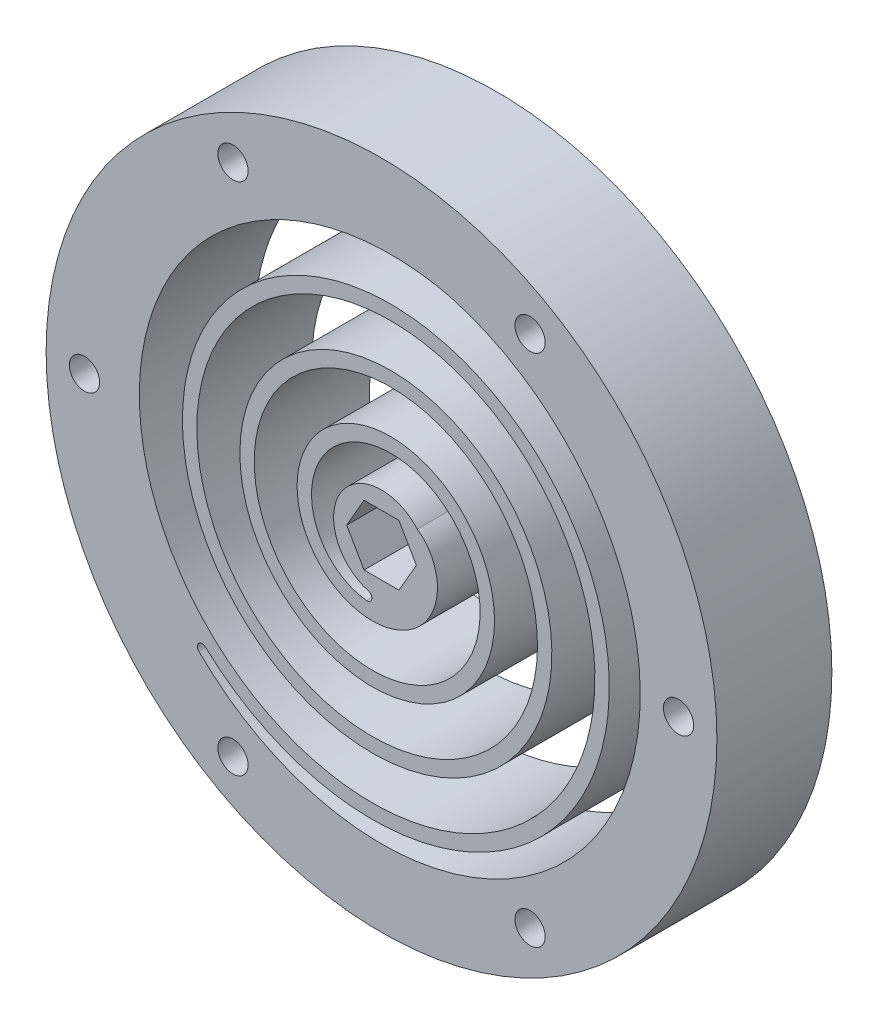
SolidWorks part; units mm, degrees
material "ASTM A36 Steel"
ref_plane "Front Plane" through (0, 0, 0) normal (0, 0, 1) x (1, 0, 0)
ref_plane "Top Plane" through (0, 0, 0) normal (0, 1, 0) x (1, 0, 0)
ref_plane "Right Plane" through (0, 0, 0) normal (1, 0, 0) x (0, 0, -1)
sketch "Sketch1" plane through (0, 0, 0) normal (0, 0, 1) x (1, 0, 0)
  line L1 (1.8187, 3.15) -> (-1.8187, 3.15)
  line L2 (-1.8187, 3.15) -> (-3.6373, 0)
  line L3 (-3.6373, 0) -> (-1.8187, -3.15)
  line L4 (-1.8187, -3.15) -> (1.8187, -3.15)
  line L5 (1.8187, -3.15) -> (3.6373, 0)
  line L6 (3.6373, 0) -> (1.8187, 3.15)
  circle A0 centre (0, 0) radius 35
  circle A1 centre (0, 0) radius 31 construction
  circle A2 centre (0, 0) radius 27
  circle A3 centre (0, 0) radius 5
  circle A4 centre (0, 0) radius 3.15 construction
  point P6 (0, 0)
  dimension "D1" = 6.3
  dimension "Spring OD" = 54
  dimension "Spring Body OD" = 70
  dimension "Bolt Centerline" = 62
  dimension "Spring ID" = 10
sketch "Sketch2" plane through (0, 0, 0) normal (0, 0, 1) x (1, 0, 0)
  line L1 (3.6373, 0) -> (1.8187, 3.15)
  line L2 (1.8187, 3.15) -> (-1.8187, 3.15)
  line L3 (-1.8187, 3.15) -> (-3.6373, 0)
  line L4 (-3.6373, 0) -> (-1.8187, -3.15)
  line L5 (-1.8187, -3.15) -> (1.8187, -3.15)
  line L6 (1.8187, -3.15) -> (3.6373, 0)
  circle A0 centre (0, 0) radius 35
  circle A1 centre (0, 0) radius 27
  circle A2 centre (0, 0) radius 5
  circle A3 centre (0, 0) radius 5 construction
  circle A4 centre (0, 0) radius 27 construction
  circle A5 centre (0, 0) radius 35 construction
  circle A6 centre (0, 0) radius 3.15 construction
  circle A7 centre (-31, 0) radius 1.58
  circle A8 centre (0, 0) radius 31 construction
  circle A9 centre (-15.5, 26.8468) radius 1.58
  circle A10 centre (15.5, 26.8468) radius 1.58
  circle A11 centre (31, 0) radius 1.58
  circle A12 centre (15.5, -26.8468) radius 1.58
  circle A13 centre (-15.5, -26.8468) radius 1.58
  point P11 (-33.4053, 32.4641)
  point P24 (0, 0)
  point P36 (0, 0)
  dimension "D1" = 3.16
  dimension "D2" = 6
extrude "Boss-Extrude1" add sketch "Sketch2" along normal blind 12 contours A0 A13 A12 A11 A10 A9 A7 A1 | A2 L6 L5 L4 L3 L2 L1
sketch "Sketch3" plane through (0, 0, 0) normal (0, 0, 1) x (1, 0, 0)
  circle A0 centre (0, 0) radius 5
  circle A1 centre (0, 0) radius 5 construction
curve "Helix/Spiral1"
sketch "Sketch6" plane through (0, 0, 0) normal (0, 0, 1) x (1, 0, 0)
  circle A0 centre (0, 0) radius 5 construction
  arc A1 (3.4915, -3.5791) -> (3.7422, 3.3161) centre (0, 0) ccw
  arc A2 (7.0031, 26.076) -> (-26.083, 6.977) centre (0, 0) ccw
  circle A3 centre (0, 0) radius 27 construction
  spline S2 degree 3 poles (656.0344, -3941.2943) (-203.1406, 58.5302) (9.6748, 22.8003) (4.1017, -2.4931) (3.8402, -3.0922) (3.0715, -4.167) (2.5594, -4.6491) (1.3478, -5.3876) (0.6412, -5.6477) (-0.8593, -5.8682) (-1.6609, -5.8292) (-3.2231, -5.4225) (-3.9909, -5.0525) (-5.3491, -4.0104) (-5.9453, -3.3335) (-6.8402, -1.7606) (-7.1423, -0.8581) (-7.3683, 1.0359) (-7.2928, 2.0345) (-6.7403, 3.9621) (-6.2609, 4.8977) (-4.944, 6.5373) (-4.1017, 7.2465) (-2.1671, 8.2957) (-1.0685, 8.6388) (1.2185, 8.8687) (2.414, 8.7559) (4.706, 8.0561) (5.8091, 7.4669) (7.7289, 5.8743) (8.5506, 4.8664) (9.753, 2.5699) (10.1365, 1.2752) (10.3691, -1.4049) (10.2185, -2.797) (9.3708, -5.453) (8.6713, -6.7232) (6.8026, -8.9225) (5.6288, -9.8564) (2.9702, -11.2112) (1.4793, -11.6348) (-1.5936, -11.8696) (-3.1822, -11.6808) (-6.202, -10.6846) (-7.6391, -9.8747) (-10.1175, -7.7295) (-11.1633, -6.3898) (-12.6701, -3.3689) (-13.1335, -1.6818) (-13.3699, 1.7839) (-13.1429, 3.569) (-11.9978, 6.9523) (-11.0773, 8.5563) (-8.6554, 11.3135) (-7.1496, 12.471) (-3.7663, 14.1294) (-1.8832, 14.6326) (1.9754, 14.8703) (3.956, 14.6052) (6.7673, 13.634) (7.6787, 13.2154) (9.4111, 12.2011) (10.2329, 11.605) (11.7515, 10.2549) (12.449, 9.5004) (13.6888, 7.8597) (14.2315, 6.9727) (15.1368, 5.099) (15.4997, 4.1114) (16.0269, 2.073) (16.1915, 1.0213) (16.3109, -1.1054) (16.2659, -2.1812) (15.9634, -4.3144) (15.7059, -5.3726) (14.9837, -7.4285) (14.5188, -8.427) (13.3959, -10.323) (12.7374, -11.2212) (11.2488, -12.879) (10.4182, -13.6393) (8.6144, -14.9885) (7.6406, -15.578) (5.5856, -16.5589) (4.5036, -16.9507) (2.2727, -17.5166) (1.1228, -17.691) (-1.2002, -17.811) (-2.3742, -17.7565) (-4.7001, -17.4162) (-5.8528, -17.1301) (-8.0903, -16.3333) (-9.1759, -15.8221) (-11.2353, -14.5904) (-12.2099, -13.8694) (-14.0069, -12.2423) (-14.8299, -11.3355) (-16.2886, -9.3687) (-16.9248, -8.3079) (-17.9812, -6.0717) (-18.4018, -4.8954) (-19.0064, -2.4719) (-19.1907, -1.2239) (-19.311, 1.2955) (-19.2471, 2.5677) (-18.8688, 5.0863) (-18.5543, 6.3334) (-17.6826, 8.7524) (-17.1251, 9.9252) (-15.7846, 12.1481) (-15.0012, 13.199) (-13.2355, 15.1351) (-12.2525, 16.0209) (-10.1226, 17.589) (-8.9749, 18.2718) (-6.5574, 19.4036) (-5.2868, 19.853) (-2.6708, 20.4963) (-1.3246, 20.6904) (1.3912, 20.811) (2.7616, 20.7376) (5.4728, 20.3213) (6.8144, 19.9784) (9.415, 19.0318) (10.6748, 18.4279) (13.0611, 16.9786) (14.1884, 16.1327) (16.2636, 14.2284) (17.2121, 13.1693) (18.8895, 10.8763) (19.6189, 9.6417) (20.8262, 7.0428) (21.3044, 5.6778) (21.9863, 2.8693) (22.1902, 1.4249) (22.3111, -1.4872) (22.2281, -2.9558) (21.7738, -5.8596) (21.4024, -7.2957) (20.3809, -10.0778) (19.7306, -11.4246) (18.1724, -13.9744) (17.2641, -15.1781) (15.2211, -17.3923) (14.0858, -18.4034) (11.6297, -20.1902) (10.3081, -20.9663) (7.528, -22.2489) (6.0686, -22.7558) (3.0675, -23.4763) (1.525, -23.69) (-1.5834, -23.8111) (-3.1503, -23.7186) (-6.2467, -23.2263) (-7.7772, -22.8263) (-10.7408, -21.7299) (-12.1748, -21.0332) (-14.8879, -19.3662) (-16.1679, -18.3953) (-18.5211, -16.2136) (-19.595, -15.0022) (-21.491, -12.3829) (-22.3137, -10.9744) (-23.6717, -8.0129) (-24.2074, -6.4591) (-24.9663, -3.2656) (-25.1898, -1.6249) (-25.3112, 1.6799) (-25.2091, 3.345) (-24.6787, 6.6341) (-24.2501, 8.259) (-23.0788, 11.4041) (-22.3357, 12.925) (-20.5597, 15.8016) (-19.5264, 17.1579) (-17.206, 19.6501) (-15.9184, 20.7866) (-13.136, 22.7919) (-11.6405, 23.6612) (-8.4977, 25.0945) (-6.8495, 25.6589) (-3.4634, 26.4564) (-1.7246, 26.6897) (1.7766, 26.8112) (3.5398, 26.6996) (7.0215, 26.131) (8.7409, 25.6739) (12.0675, 24.4277) (13.6755, 23.6382) (16.7154, 21.7532) (18.1481, 20.6574) (20.7792, 18.1983) (21.9784, 16.8344) (24.0929, 13.8889) (25.0088, 12.3064) (26.5174, 8.9823) (27.1106, 7.2398) (47.698, -80.8932) (-339.5507, -278.2314) (-1939.009, 3446.9436) knots -0.630078 -0.630078 -0.630078 -0.630078 0.015625 0.015625 0.03125 0.03125 0.046875 0.046875 0.0625 0.0625 0.078125 0.078125 0.09375 0.09375 0.109375 0.109375 0.125 0.125 0.140625 0.140625 0.15625 0.15625 0.171875 0.171875 0.1875 0.1875 0.203125 0.203125 0.21875 0.21875 0.234375 0.234375 0.25 0.25 0.265625 0.265625 0.28125 0.28125 0.296875 0.296875 0.3125 0.3125 0.328125 0.328125 0.34375 0.34375 0.359375 0.359375 0.375 0.375 0.390625 0.390625 0.40625 0.40625 0.421875 0.421875 0.4375 0.4375 0.453125 0.453125 0.460938 0.460938 0.46875 0.46875 0.476563 0.476563 0.484375 0.484375 0.492188 0.492188 0.5 0.5 0.507813 0.507813 0.515625 0.515625 0.523438 0.523438 0.53125 0.53125 0.539063 0.539063 0.546875 0.546875 0.554688 0.554688 0.5625 0.5625 0.570313 0.570313 0.578125 0.578125 0.585938 0.585938 0.59375 0.59375 0.601563 0.601563 0.609375 0.609375 0.617188 0.617188 0.625 0.625 0.632813 0.632813 0.640625 0.640625 0.648438 0.648438 0.65625 0.65625 0.664063 0.664063 0.671875 0.671875 0.679688 0.679688 0.6875 0.6875 0.695313 0.695313 0.703125 0.703125 0.710938 0.710938 0.71875 0.71875 0.726563 0.726563 0.734375 0.734375 0.742188 0.742188 0.75 0.75 0.757813 0.757813 0.765625 0.765625 0.773438 0.773438 0.78125 0.78125 0.789063 0.789063 0.796875 0.796875 0.804688 0.804688 0.8125 0.8125 0.820313 0.820313 0.828125 0.828125 0.835938 0.835938 0.84375 0.84375 0.851563 0.851563 0.859375 0.859375 0.867188 0.867188 0.875 0.875 0.882813 0.882813 0.890625 0.890625 0.898438 0.898438 0.90625 0.90625 0.914063 0.914063 0.921875 0.921875 0.929688 0.929688 0.9375 0.9375 0.945312 0.945312 0.953125 0.953125 0.960938 0.960938 0.96875 0.96875 0.976562 0.976562 0.984375 0.984375 0.992188 0.992188 1.369176 1.369176 1.369176 1.369176 only from (4.2633, -0.1407) to (28.2504, -0.0247)
  spline S3 degree 3 poles (3.4915, -3.5791) (3.4797, -3.596) (3.4678, -3.6128) (3.0715, -4.167) (2.5594, -4.6491) (1.3478, -5.3876) (0.6412, -5.6477) (-0.8593, -5.8682) (-1.6609, -5.8292) (-3.2231, -5.4225) (-3.9909, -5.0525) (-5.3491, -4.0104) (-5.9453, -3.3335) (-6.8402, -1.7606) (-7.1423, -0.8581) (-7.3683, 1.0359) (-7.2928, 2.0345) (-6.7403, 3.9621) (-6.2609, 4.8977) (-4.944, 6.5373) (-4.1017, 7.2465) (-2.1671, 8.2957) (-1.0685, 8.6388) (1.2185, 8.8687) (2.414, 8.7559) (4.706, 8.0561) (5.8091, 7.4669) (7.7289, 5.8743) (8.5506, 4.8664) (9.753, 2.5699) (10.1365, 1.2752) (10.3691, -1.4049) (10.2185, -2.797) (9.3708, -5.453) (8.6713, -6.7232) (6.8026, -8.9225) (5.6288, -9.8564) (2.9702, -11.2112) (1.4793, -11.6348) (-1.5936, -11.8696) (-3.1822, -11.6808) (-6.202, -10.6846) (-7.6391, -9.8747) (-10.1175, -7.7295) (-11.1633, -6.3898) (-12.6701, -3.3689) (-13.1335, -1.6818) (-13.3699, 1.7839) (-13.1429, 3.569) (-11.9978, 6.9523) (-11.0773, 8.5563) (-8.6554, 11.3135) (-7.1496, 12.471) (-3.7663, 14.1294) (-1.8832, 14.6326) (1.9754, 14.8703) (3.956, 14.6052) (6.7673, 13.634) (7.6787, 13.2154) (9.4111, 12.2011) (10.2329, 11.605) (11.7515, 10.2549) (12.449, 9.5004) (13.6888, 7.8597) (14.2315, 6.9727) (15.1368, 5.099) (15.4997, 4.1114) (16.0269, 2.073) (16.1915, 1.0213) (16.3109, -1.1054) (16.2659, -2.1812) (15.9634, -4.3144) (15.7059, -5.3726) (14.9837, -7.4285) (14.5188, -8.427) (13.3959, -10.323) (12.7374, -11.2212) (11.2488, -12.879) (10.4182, -13.6393) (8.6144, -14.9885) (7.6406, -15.578) (5.5856, -16.5589) (4.5036, -16.9507) (2.2727, -17.5166) (1.1228, -17.691) (-1.2002, -17.811) (-2.3742, -17.7565) (-4.7001, -17.4162) (-5.8528, -17.1301) (-8.0903, -16.3333) (-9.1759, -15.8221) (-11.2353, -14.5904) (-12.2099, -13.8694) (-14.0069, -12.2423) (-14.8299, -11.3355) (-16.2886, -9.3687) (-16.9248, -8.3079) (-17.9812, -6.0717) (-18.4018, -4.8954) (-19.0064, -2.4719) (-19.1907, -1.2239) (-19.311, 1.2955) (-19.2471, 2.5677) (-18.8688, 5.0863) (-18.5543, 6.3334) (-17.6826, 8.7524) (-17.1251, 9.9252) (-15.7846, 12.1481) (-15.0012, 13.199) (-13.2355, 15.1351) (-12.2525, 16.0209) (-10.1226, 17.589) (-8.9749, 18.2718) (-6.5574, 19.4036) (-5.2868, 19.853) (-2.6708, 20.4963) (-1.3246, 20.6904) (1.3912, 20.811) (2.7616, 20.7376) (5.4728, 20.3213) (6.8144, 19.9784) (9.415, 19.0318) (10.6748, 18.4279) (13.0611, 16.9786) (14.1884, 16.1327) (16.2636, 14.2284) (17.2121, 13.1693) (18.8895, 10.8763) (19.6189, 9.6417) (20.8262, 7.0428) (21.3044, 5.6778) (21.9863, 2.8693) (22.1902, 1.4249) (22.3111, -1.4872) (22.2281, -2.9558) (21.7738, -5.8596) (21.4024, -7.2957) (20.3809, -10.0778) (19.7306, -11.4246) (18.1724, -13.9744) (17.2641, -15.1781) (15.2211, -17.3923) (14.0858, -18.4034) (11.6297, -20.1902) (10.3081, -20.9663) (7.528, -22.2489) (6.0686, -22.7558) (3.0675, -23.4763) (1.525, -23.69) (-1.5834, -23.8111) (-3.1503, -23.7186) (-6.2467, -23.2263) (-7.7772, -22.8263) (-10.7408, -21.7299) (-12.1748, -21.0332) (-14.8879, -19.3662) (-16.1679, -18.3953) (-18.5211, -16.2136) (-19.595, -15.0022) (-21.491, -12.3829) (-22.3137, -10.9744) (-23.6717, -8.0129) (-24.2074, -6.4591) (-24.9663, -3.2656) (-25.1898, -1.6249) (-25.3112, 1.6799) (-25.2091, 3.345) (-24.6787, 6.6341) (-24.2501, 8.259) (-23.0788, 11.4041) (-22.3357, 12.925) (-20.5597, 15.8016) (-19.5264, 17.1579) (-17.206, 19.6501) (-15.9184, 20.7866) (-13.136, 22.7919) (-11.6405, 23.6612) (-8.4977, 25.0945) (-6.8495, 25.6589) (-3.4634, 26.4564) (-1.7246, 26.6897) (1.7766, 26.8112) (3.5398, 26.6996) (5.8576, 26.3211) (6.4322, 26.2079) (7.0031, 26.076) knots 0.030762 0.030762 0.030762 0.030762 0.03125 0.03125 0.046875 0.046875 0.0625 0.0625 0.078125 0.078125 0.09375 0.09375 0.109375 0.109375 0.125 0.125 0.140625 0.140625 0.15625 0.15625 0.171875 0.171875 0.1875 0.1875 0.203125 0.203125 0.21875 0.21875 0.234375 0.234375 0.25 0.25 0.265625 0.265625 0.28125 0.28125 0.296875 0.296875 0.3125 0.3125 0.328125 0.328125 0.34375 0.34375 0.359375 0.359375 0.375 0.375 0.390625 0.390625 0.40625 0.40625 0.421875 0.421875 0.4375 0.4375 0.453125 0.453125 0.460938 0.460938 0.46875 0.46875 0.476563 0.476563 0.484375 0.484375 0.492188 0.492188 0.5 0.5 0.507813 0.507813 0.515625 0.515625 0.523438 0.523438 0.53125 0.53125 0.539063 0.539063 0.546875 0.546875 0.554688 0.554688 0.5625 0.5625 0.570313 0.570313 0.578125 0.578125 0.585938 0.585938 0.59375 0.59375 0.601563 0.601563 0.609375 0.609375 0.617188 0.617188 0.625 0.625 0.632813 0.632813 0.640625 0.640625 0.648438 0.648438 0.65625 0.65625 0.664063 0.664063 0.671875 0.671875 0.679688 0.679688 0.6875 0.6875 0.695313 0.695313 0.703125 0.703125 0.710938 0.710938 0.71875 0.71875 0.726563 0.726563 0.734375 0.734375 0.742188 0.742188 0.75 0.75 0.757813 0.757813 0.765625 0.765625 0.773438 0.773438 0.78125 0.78125 0.789063 0.789063 0.796875 0.796875 0.804688 0.804688 0.8125 0.8125 0.820313 0.820313 0.828125 0.828125 0.835938 0.835938 0.84375 0.84375 0.851563 0.851563 0.859375 0.859375 0.867188 0.867188 0.875 0.875 0.882813 0.882813 0.890625 0.890625 0.898438 0.898438 0.90625 0.90625 0.914063 0.914063 0.921875 0.921875 0.929688 0.929688 0.9375 0.9375 0.945312 0.945312 0.947902 0.947902 0.947902 0.947902
  spline S4 degree 3 poles (435.9917, -3966.6202) (-274.7146, 76.6016) (13.0478, 31.1372) (5.5224, -3.0164) (5.1792, -3.7983) (4.1726, -5.2059) (3.5142, -5.8238) (1.9543, -6.7746) (1.0605, -7.1023) (-0.8424, -7.3818) (-1.8425, -7.3319) (-3.7973, -6.823) (-4.7433, -6.3659) (-6.4228, -5.0773) (-7.149, -4.251) (-8.2439, -2.3267) (-8.6077, -1.2363) (-8.8817, 1.0585) (-8.7903, 2.2541) (-8.1266, 4.5692) (-7.5565, 5.68) (-5.9873, 7.6336) (-4.9937, 8.4691) (-2.7054, 9.7102) (-1.4186, 10.1112) (1.2685, 10.3813) (2.6599, 10.2491) (5.3361, 9.4321) (6.6123, 8.7495) (8.8411, 6.9007) (9.7864, 5.7399) (11.1749, 3.0879) (11.6135, 1.6046) (11.8809, -1.4749) (11.7084, -3.0621) (10.7388, -6.1) (9.9441, -7.5418) (7.816, -10.0464) (6.4883, -11.102) (3.4729, -12.6386) (1.7932, -13.1152) (-1.6789, -13.3804) (-3.4621, -13.168) (-6.8619, -12.0464) (-8.4696, -11.1397) (-11.2504, -8.7328) (-12.4164, -7.2382) (-14.1016, -3.8594) (-14.6165, -1.9833) (-14.8801, 1.8813) (-14.6278, 3.8606) (-13.3545, 7.6225) (-12.3361, 9.3961) (-9.6505, 12.4535) (-7.9892, 13.73) (-4.2472, 15.5642) (-2.1747, 16.1174) (2.0825, 16.3797) (4.2589, 16.0875) (7.3505, 15.0195) (8.3513, 14.5598) (10.2543, 13.4456) (11.1556, 12.7917) (12.822, 11.3103) (13.5862, 10.4836) (14.9451, 8.6851) (15.5392, 7.7142) (16.5304, 5.6625) (16.9272, 4.5826) (17.5039, 2.3529) (17.6835, 1.204) (17.8141, -1.1199) (17.7649, -2.294) (17.4347, -4.6228) (17.1538, -5.7765) (16.3662, -8.0188) (15.8598, -9.1064) (14.6362, -11.1724) (13.9195, -12.1498) (12.2989, -13.9546) (11.3958, -14.7813) (9.4338, -16.2488) (8.3758, -16.8892) (6.1426, -17.9552) (4.9682, -18.3803) (2.5458, -18.9949) (1.2988, -19.184) (-1.2215, -19.314) (-2.4937, -19.255) (-5.015, -18.8861) (-6.263, -18.5763) (-8.6865, -17.7132) (-9.861, -17.1601) (-12.09, -15.827) (-13.1435, -15.0476) (-15.0869, -13.2879) (-15.9759, -12.3084) (-17.5523, -10.183) (-18.2389, -9.0379) (-19.3796, -6.6231) (-19.8333, -5.3543) (-20.4857, -2.7393) (-20.6843, -1.3941) (-20.814, 1.3225) (-20.7451, 2.6929) (-20.3375, 5.4067) (-19.9989, 6.7491) (-19.0603, 9.3538) (-18.4606, 10.6152) (-17.0181, 13.0072) (-16.176, 14.1369) (-14.2772, 16.2188) (-13.2213, 17.1703) (-10.9325, 18.8554) (-9.7004, 19.5884) (-7.104, 20.804) (-5.7408, 21.2861) (-2.9331, 21.9765) (-1.4897, 22.1846) (1.4232, 22.314) (2.8917, 22.2352) (5.798, 21.789) (7.2347, 21.4217) (10.0207, 20.4076) (11.3691, 19.7612) (13.9241, 18.2095) (15.13, 17.3046) (17.3505, 15.2668) (18.3645, 14.1346) (20.1584, 11.6823) (20.9378, 10.3631) (22.2282, 7.5853) (22.7388, 6.1276) (23.4672, 3.1273) (23.6848, 1.5857) (23.8139, -1.5235) (23.7253, -3.0902) (23.2405, -6.189) (22.8445, -7.7201) (21.755, -10.6874) (21.062, -12.1226) (19.4009, -14.8408) (18.4334, -16.1228) (16.2566, -18.482) (15.048, -19.5584) (12.4323, -21.4612) (11.0261, -22.287) (8.0668, -23.6523) (6.5146, -24.1914) (3.3218, -24.9579) (1.682, -25.185) (-1.6236, -25.3139) (-3.2884, -25.2155) (-6.5797, -24.6922) (-8.2052, -24.2673) (-11.3538, -23.1025) (-12.876, -22.3629) (-15.7572, -20.5925) (-17.1154, -19.5623) (-19.6133, -17.2465) (-20.7522, -15.9616) (-22.7639, -13.1826) (-23.636, -11.6893) (-25.0763, -8.5485) (-25.6439, -6.9019) (-26.4485, -3.5164) (-26.6852, -1.7785) (-26.8138, 1.7234) (-26.7057, 3.4864) (-26.1438, 6.9703) (-25.6902, 8.6901) (-24.4501, 12.02) (-23.6639, 13.6291) (-21.7843, 16.6735) (-20.6914, 18.1079) (-18.2366, 20.7445) (-16.8754, 21.9459) (-13.933, 24.0665) (-12.3526, 24.985) (-9.0304, 26.5002) (-7.2894, 27.0964) (-3.7113, 27.9391) (-1.8752, 28.1853) (1.8231, 28.3138) (3.6843, 28.1959) (7.3606, 27.5955) (9.1748, 27.1132) (12.686, 25.7977) (14.3821, 24.965) (17.5897, 22.9761) (19.1003, 21.8206) (21.8755, 19.2268) (23.1394, 17.7893) (25.3689, 14.6835) (26.3339, 13.0161) (27.9241, 9.5124) (28.5488, 7.677) (50.211, -85.0568) (-357.1086, -289.5335) (-1994.3121, 3410.461) knots -0.637379 -0.637379 -0.637379 -0.637379 0.015625 0.015625 0.03125 0.03125 0.046875 0.046875 0.0625 0.0625 0.078125 0.078125 0.09375 0.09375 0.109375 0.109375 0.125 0.125 0.140625 0.140625 0.15625 0.15625 0.171875 0.171875 0.1875 0.1875 0.203125 0.203125 0.21875 0.21875 0.234375 0.234375 0.25 0.25 0.265625 0.265625 0.28125 0.28125 0.296875 0.296875 0.3125 0.3125 0.328125 0.328125 0.34375 0.34375 0.359375 0.359375 0.375 0.375 0.390625 0.390625 0.40625 0.40625 0.421875 0.421875 0.4375 0.4375 0.453125 0.453125 0.460937 0.460937 0.46875 0.46875 0.476562 0.476562 0.484375 0.484375 0.492187 0.492187 0.5 0.5 0.507812 0.507812 0.515625 0.515625 0.523437 0.523437 0.53125 0.53125 0.539062 0.539062 0.546875 0.546875 0.554687 0.554687 0.5625 0.5625 0.570312 0.570312 0.578125 0.578125 0.585937 0.585937 0.59375 0.59375 0.601562 0.601562 0.609375 0.609375 0.617187 0.617187 0.625 0.625 0.632812 0.632812 0.640625 0.640625 0.648437 0.648437 0.65625 0.65625 0.664062 0.664062 0.671875 0.671875 0.679687 0.679687 0.6875 0.6875 0.695312 0.695312 0.703125 0.703125 0.710937 0.710937 0.71875 0.71875 0.726562 0.726562 0.734375 0.734375 0.742187 0.742187 0.75 0.75 0.757812 0.757812 0.765625 0.765625 0.773437 0.773437 0.78125 0.78125 0.789062 0.789062 0.796875 0.796875 0.804687 0.804687 0.8125 0.8125 0.820312 0.820312 0.828125 0.828125 0.835937 0.835937 0.84375 0.84375 0.851562 0.851562 0.859375 0.859375 0.867187 0.867187 0.875 0.875 0.882812 0.882812 0.890625 0.890625 0.898437 0.898437 0.90625 0.90625 0.914062 0.914062 0.921875 0.921875 0.929687 0.929687 0.9375 0.9375 0.945312 0.945312 0.953125 0.953125 0.960937 0.960937 0.96875 0.96875 0.976562 0.976562 0.984375 0.984375 0.992188 0.992188 1.368644 1.368644 1.368644 1.368644 only from (5.7367, 0.1407) to (29.7496, 0.0247)
  spline S5 degree 3 poles (3.7422, 3.3161) (5.4056, 2.1726) (6.1764, -0.0485) (5.5224, -3.0164) (5.1792, -3.7983) (4.1726, -5.2059) (3.5142, -5.8238) (1.9543, -6.7746) (1.0605, -7.1023) (-0.8424, -7.3818) (-1.8425, -7.3319) (-3.7973, -6.823) (-4.7433, -6.3659) (-6.4228, -5.0773) (-7.149, -4.251) (-8.2439, -2.3267) (-8.6077, -1.2363) (-8.8817, 1.0585) (-8.7903, 2.2541) (-8.1266, 4.5692) (-7.5565, 5.68) (-5.9873, 7.6336) (-4.9937, 8.4691) (-2.7054, 9.7102) (-1.4186, 10.1112) (1.2685, 10.3813) (2.6599, 10.2491) (5.3361, 9.4321) (6.6123, 8.7495) (8.8411, 6.9007) (9.7864, 5.7399) (11.1749, 3.0879) (11.6135, 1.6046) (11.8809, -1.4749) (11.7084, -3.0621) (10.7388, -6.1) (9.9441, -7.5418) (7.816, -10.0464) (6.4883, -11.102) (3.4729, -12.6386) (1.7932, -13.1152) (-1.6789, -13.3804) (-3.4621, -13.168) (-6.8619, -12.0464) (-8.4696, -11.1397) (-11.2504, -8.7328) (-12.4164, -7.2382) (-14.1016, -3.8594) (-14.6165, -1.9833) (-14.8801, 1.8813) (-14.6278, 3.8606) (-13.3545, 7.6225) (-12.3361, 9.3961) (-9.6505, 12.4535) (-7.9892, 13.73) (-4.2472, 15.5642) (-2.1747, 16.1174) (2.0825, 16.3797) (4.2589, 16.0875) (7.3505, 15.0195) (8.3513, 14.5598) (10.2543, 13.4456) (11.1556, 12.7917) (12.822, 11.3103) (13.5862, 10.4836) (14.9451, 8.6851) (15.5392, 7.7142) (16.5304, 5.6625) (16.9272, 4.5826) (17.5039, 2.3529) (17.6835, 1.204) (17.8141, -1.1199) (17.7649, -2.294) (17.4347, -4.6228) (17.1538, -5.7765) (16.3662, -8.0188) (15.8598, -9.1064) (14.6362, -11.1724) (13.9195, -12.1498) (12.2989, -13.9546) (11.3958, -14.7813) (9.4338, -16.2488) (8.3758, -16.8892) (6.1426, -17.9552) (4.9682, -18.3803) (2.5458, -18.9949) (1.2988, -19.184) (-1.2215, -19.314) (-2.4937, -19.255) (-5.015, -18.8861) (-6.263, -18.5763) (-8.6865, -17.7132) (-9.861, -17.1601) (-12.09, -15.827) (-13.1435, -15.0476) (-15.0869, -13.2879) (-15.9759, -12.3084) (-17.5523, -10.183) (-18.2389, -9.0379) (-19.3796, -6.6231) (-19.8333, -5.3543) (-20.4857, -2.7393) (-20.6843, -1.3941) (-20.814, 1.3225) (-20.7451, 2.6929) (-20.3375, 5.4067) (-19.9989, 6.7491) (-19.0603, 9.3538) (-18.4606, 10.6152) (-17.0181, 13.0072) (-16.176, 14.1369) (-14.2772, 16.2188) (-13.2213, 17.1703) (-10.9325, 18.8554) (-9.7004, 19.5884) (-7.104, 20.804) (-5.7408, 21.2861) (-2.9331, 21.9765) (-1.4897, 22.1846) (1.4232, 22.314) (2.8917, 22.2352) (5.798, 21.789) (7.2347, 21.4217) (10.0207, 20.4076) (11.3691, 19.7612) (13.9241, 18.2095) (15.13, 17.3046) (17.3505, 15.2668) (18.3645, 14.1346) (20.1584, 11.6823) (20.9378, 10.3631) (22.2282, 7.5853) (22.7388, 6.1276) (23.4672, 3.1273) (23.6848, 1.5857) (23.8139, -1.5235) (23.7253, -3.0902) (23.2405, -6.189) (22.8445, -7.7201) (21.755, -10.6874) (21.062, -12.1226) (19.4009, -14.8408) (18.4334, -16.1228) (16.2566, -18.482) (15.048, -19.5584) (12.4323, -21.4612) (11.0261, -22.287) (8.0668, -23.6523) (6.5146, -24.1914) (3.3218, -24.9579) (1.682, -25.185) (-1.6236, -25.3139) (-3.2884, -25.2155) (-6.5797, -24.6922) (-8.2052, -24.2673) (-11.3538, -23.1025) (-12.876, -22.3629) (-15.7572, -20.5925) (-17.1154, -19.5623) (-19.6133, -17.2465) (-20.7522, -15.9616) (-22.7639, -13.1826) (-23.636, -11.6893) (-25.0763, -8.5485) (-25.6439, -6.9019) (-26.4485, -3.5164) (-26.6852, -1.7785) (-26.8138, 1.7234) (-26.7057, 3.4864) (-26.3303, 5.8141) (-26.2163, 6.3974) (-26.083, 6.977) knots -0.026854 -0.026854 -0.026854 -0.026854 0.015625 0.015625 0.03125 0.03125 0.046875 0.046875 0.0625 0.0625 0.078125 0.078125 0.09375 0.09375 0.109375 0.109375 0.125 0.125 0.140625 0.140625 0.15625 0.15625 0.171875 0.171875 0.1875 0.1875 0.203125 0.203125 0.21875 0.21875 0.234375 0.234375 0.25 0.25 0.265625 0.265625 0.28125 0.28125 0.296875 0.296875 0.3125 0.3125 0.328125 0.328125 0.34375 0.34375 0.359375 0.359375 0.375 0.375 0.390625 0.390625 0.40625 0.40625 0.421875 0.421875 0.4375 0.4375 0.453125 0.453125 0.460937 0.460937 0.46875 0.46875 0.476562 0.476562 0.484375 0.484375 0.492187 0.492187 0.5 0.5 0.507812 0.507812 0.515625 0.515625 0.523437 0.523437 0.53125 0.53125 0.539062 0.539062 0.546875 0.546875 0.554687 0.554687 0.5625 0.5625 0.570312 0.570312 0.578125 0.578125 0.585937 0.585937 0.59375 0.59375 0.601562 0.601562 0.609375 0.609375 0.617187 0.617187 0.625 0.625 0.632812 0.632812 0.640625 0.640625 0.648437 0.648437 0.65625 0.65625 0.664062 0.664062 0.671875 0.671875 0.679687 0.679687 0.6875 0.6875 0.695312 0.695312 0.703125 0.703125 0.710937 0.710937 0.71875 0.71875 0.726562 0.726562 0.734375 0.734375 0.742187 0.742187 0.75 0.75 0.757812 0.757812 0.765625 0.765625 0.773437 0.773437 0.78125 0.78125 0.789062 0.789062 0.796875 0.796875 0.804687 0.804687 0.8125 0.8125 0.820312 0.820312 0.828125 0.828125 0.835937 0.835937 0.84375 0.84375 0.851562 0.851562 0.859375 0.859375 0.867187 0.867187 0.875 0.875 0.882812 0.882812 0.88544 0.88544 0.88544 0.88544
  point P11 (4.4006, 2.7621)
  point P12 (-4.3368, 27.7658)
  point P13 (-2.1564, 26.5848)
  point P19 (4.8232, 26.5657)
  point P20 (-19.0905, 19.0933)
  point P21 (0, 0)
  point P22 (0, 0)
  point P23 (0, 0)
  point P24 (4.1162, 3.0283)
  point P25 (0, 0)
  point P26 (0, 0)
  point P27 (0, 0)
  point P28 (0, 0)
  dimension "D1" = 0.75
  dimension "D2" = 0.75
extrude "Boss-Extrude2" add sketch "Sketch6" along normal up to surface (12 mm away) up to face at (-13.92, -26.8468, 12)
fillet "Fillet1" radius 0.5 2 edges
equation "\"b\"= 12mm"
equation "\"D1@Boss-Extrude1\"=\"b\""
equation "\"t\"= 1.5mm"
equation "\"D2@Sketch6\"=\"t\"/2"
equation "\"D1@Sketch6\"=\"t\"/2"
